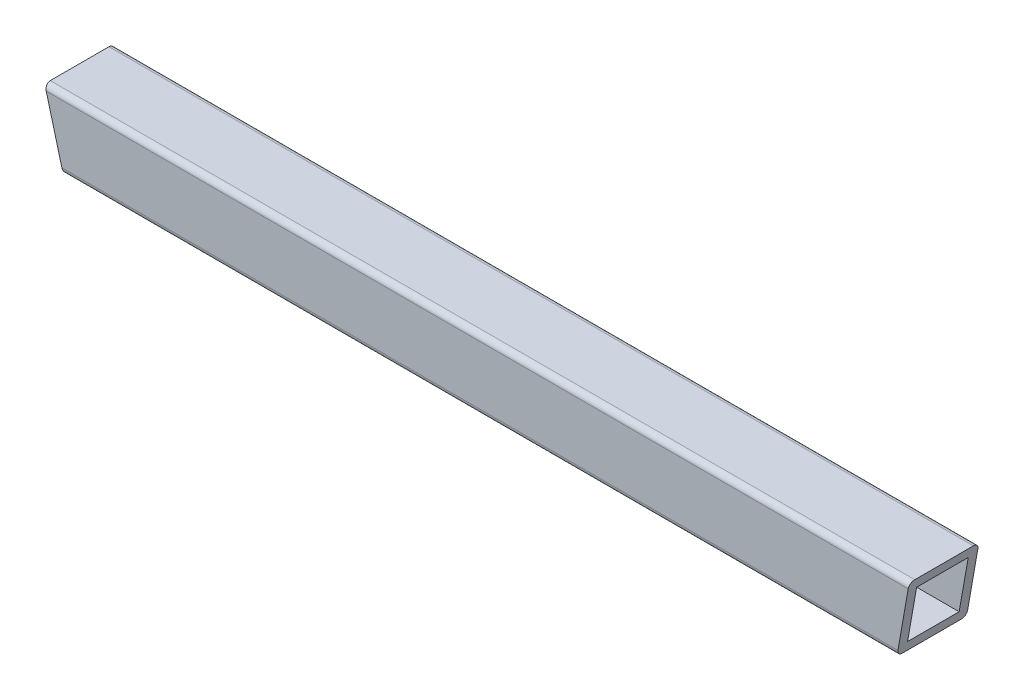
SolidWorks part; units mm, degrees
material "Plain Carbon Steel"
ref_plane "Front Plane" through (0, 0, 0) normal (0, 0, 1) x (1, 0, 0)
ref_plane "Top Plane" through (0, 0, 0) normal (0, 1, 0) x (1, 0, 0)
ref_plane "Right Plane" through (0, 0, 0) normal (1, 0, 0) x (0, 0, -1)
sketch "Sketch1" plane through (0, 0, 0) normal (1, 0, 0) x (0, 0, -1)
  line L0 (0, 2.54) -> (0, 29.21)
  line L1 (-2.54, 31.75) -> (-29.21, 31.75)
  line L2 (-31.75, 29.21) -> (-31.75, 2.54)
  line L3 (-29.21, 0) -> (-2.54, 0)
  line L4 (-4.1275, 4.1275) -> (-4.1275, 27.6225)
  line L5 (-4.1275, 27.6225) -> (-27.6225, 27.6225)
  line L6 (-27.6225, 27.6225) -> (-27.6225, 4.1275)
  line L7 (-27.6225, 4.1275) -> (-4.1275, 4.1275)
  arc A0 (-31.75, 2.54) -> (-29.21, 0) centre (-29.21, 2.54) ccw
  arc A1 (0, 2.54) -> (-2.54, 0) centre (-2.54, 2.54) cw
  arc A2 (0, 29.21) -> (-2.54, 31.75) centre (-2.54, 29.21) ccw
  arc A3 (-31.75, 29.21) -> (-29.21, 31.75) centre (-29.21, 29.21) cw
  arc A4 (-4.1275, 27.6225) -> (-4.1275, 27.6225) centre (-4.1275, 27.6225) ccw
  arc A5 (-27.6225, 27.6225) -> (-27.6225, 27.6225) centre (-27.6225, 27.6225) cw
  arc A6 (-27.6225, 4.1275) -> (-27.6225, 4.1275) centre (-27.6225, 4.1275) ccw
  arc A7 (-4.1275, 4.1275) -> (-4.1275, 4.1275) centre (-4.1275, 4.1275) cw
  point P12 (0, 0)
  point P15 (0, 31.75)
  point P18 (-31.75, 31.75)
  dimension "D3" = 2.54
  dimension "D1" = 31.75
  dimension "D2" = 31.75
  dimension "D4" = 4.1275
extrude "Boss-Extrude1" add sketch "Sketch1" along normal blind 393.7
scale "Scale1" scale about centroid uniform scaling no x scale factor 1 y scale factor 0.4 z scale factor 0.4
sketch "Sketch4" plane through (0, 0, 9.525) normal (0, 0, -1) x (-1, 0, 0)
  line L0 (-393.7, 15.875) -> (0, 15.875) construction
  line L1 (-393.7, 10.541) -> (-393.7, 21.209) construction
  line L2 (0, 10.541) -> (0, 21.209) construction
sketch "Sketch5" plane through (0, 0, 9.525) normal (0, 0, -1) x (-1, 0, 0)
  line L2 (-393.7, 9.525) -> (0, 9.525) construction
  line L5 (-393.7, 22.225) -> (0, 22.225) construction
  line L16 (-195.5004, 9.525) -> (-192.0975, 22.225)
  line L18 (-192.0975, 22.225) -> (-165.1271, 22.225)
  line L19 (-165.1271, 22.225) -> (-162.8877, 9.525)
  line L20 (-162.8877, 9.525) -> (-195.5004, 9.525)
  line L21 (-199.664, 218.094) -> (-112.1562, -278.1874) construction
  line L22 (-11.019, 9.525) -> (0, 9.525)
  line L23 (15.5089, 108.5285) -> (-86.2514, -271.2462) construction
  line L24 (0, 9.525) -> (0, 22.225)
  line L25 (0, 22.225) -> (-7.616, 22.225)
  line L26 (-7.616, 22.225) -> (-11.019, 9.525)
extrude "Cut-Extrude3" cut sketch "Sketch5" against normal through all
